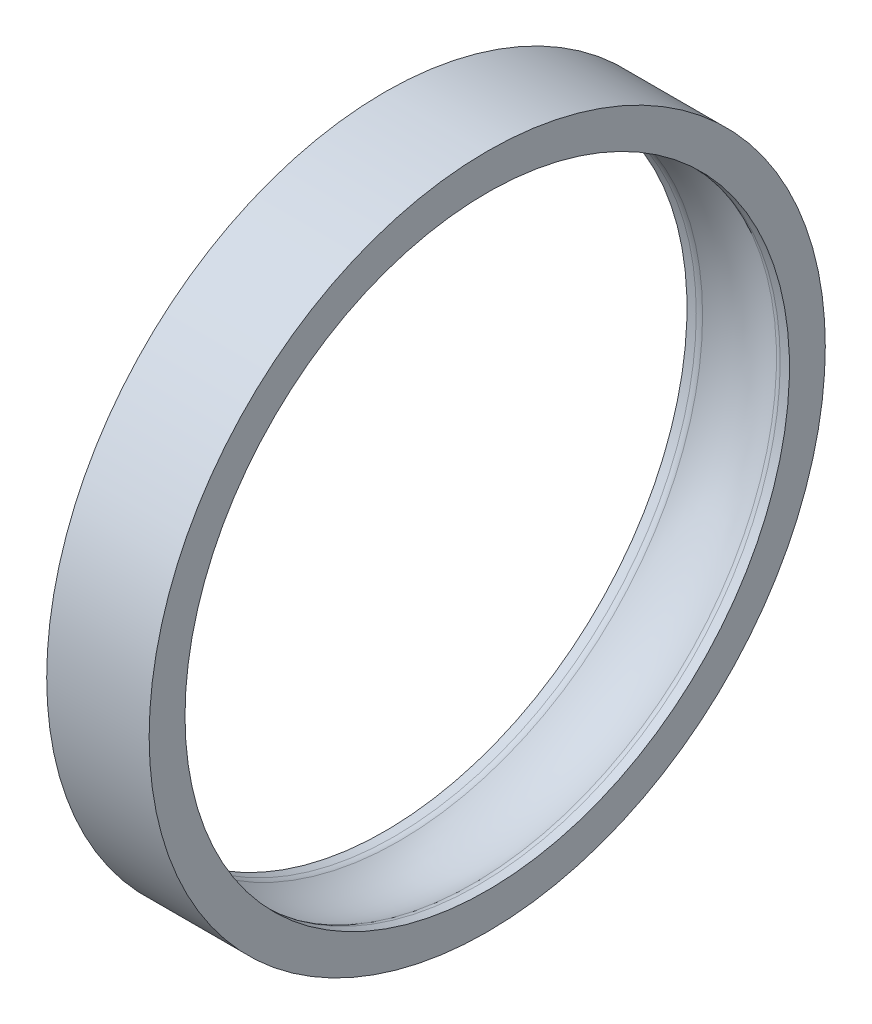
SolidWorks part; units mm, degrees
ref_plane "Front Plane" through (0, 0, 0) normal (0, 0, 1) x (1, 0, 0)
ref_plane "Top Plane" through (0, 0, 0) normal (0, 1, 0) x (1, 0, 0)
ref_plane "Right Plane" through (0, 0, 0) normal (1, 0, 0) x (0, 0, -1)
sketch "Sketch1" plane through (0, 0, 0) normal (0, 0, 1) x (1, 0, 0)
  line L1 (-10, 66) -> (10, 66)
  line L2 (-10, 66) -> (-10, 59)
  line L3 (-10, 59) -> (-7.6531, 59)
  line L4 (10, 66) -> (10, 59)
  line L7 (7.6531, 59) -> (10, 59)
  arc A0 (7.6531, 59) -> (-7.6531, 59) centre (0, 46.4197) ccw
  point P0 (0, 62.5)
  dimension "D1" = 20
  dimension "D2" = 7
revolve "Revolve5" add sketch "Sketch1" angle 360 about L0
fillet "Fillet1" radius 2 2 edges at (7.6531, 0, 59) (-7.6531, 0, 59)
sketch "Sketch9" plane through (0, 0, 0) normal (0, 0, 1) x (1, 0, 0)
  line L0 (-1000, 0) -> (49000, 0) construction
sketch "Sketch5" plane through (0, 0, 0) normal (0, 0, 1) x (1, 0, 0)
  line L0 (-1000, 0) -> (49000, 0) construction
  line L1 (-4.25, 55.5) -> (4.25, 55.5)
  circle A0 centre (0, 55.5) radius 4.25 construction
sketch "Sketch8" plane through (0, 0, 0) normal (0, 0, 1) x (1, 0, 0)
